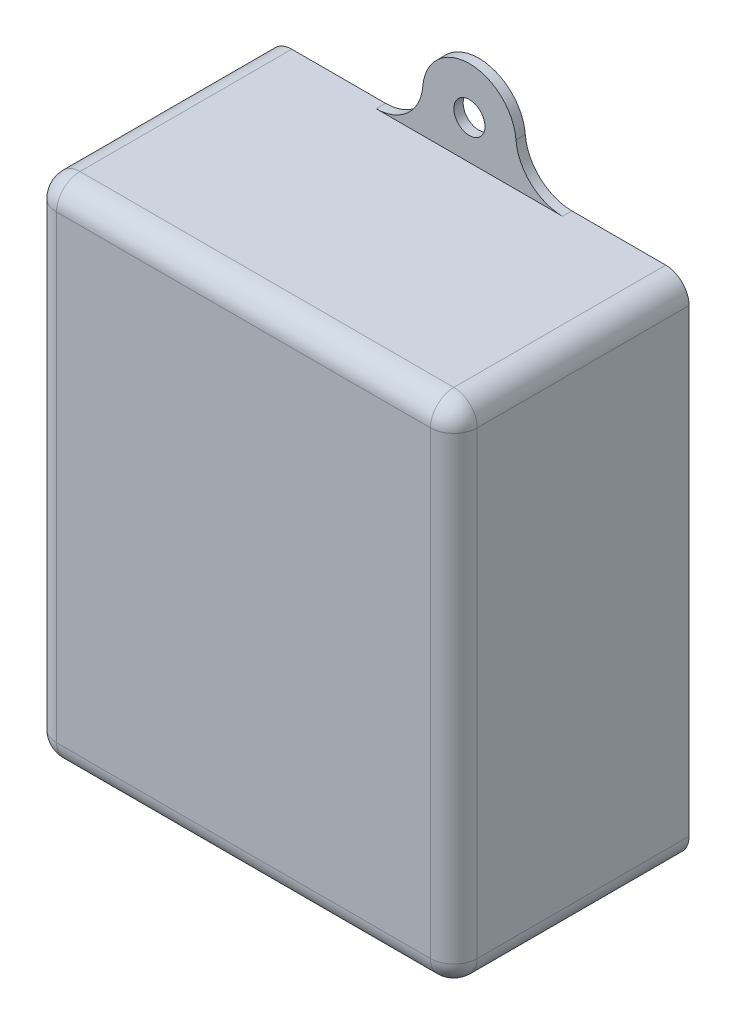
SolidWorks part; units mm, degrees
ref_plane "前视基准面" through (0, 0, 0) normal (0, 0, 1) x (1, 0, 0)
ref_plane "上视基准面" through (0, 0, 0) normal (0, 1, 0) x (1, 0, 0)
ref_plane "右视基准面" through (0, 0, 0) normal (1, 0, 0) x (0, 0, -1)
sketch "草图1" plane through (0, 0, 0) normal (0, 0, 1) x (1, 0, 0)
  line L0 (-11.9583, 32.5) -> (-27, 32.5)
  line L1 (-27, 32.5) -> (-27, -32.5)
  line L3 (27, -32.5) -> (27, 32.5)
  line L4 (-62.2008, 0) -> (42.7389, 0) construction
  line L5 (0, 66.4186) -> (0, -56.2887) construction
  line L6 (11.9583, 32.5) -> (27, 32.5)
  line L7 (-11.9583, -32.5) -> (-27, -32.5)
  line L8 (11.9583, -32.5) -> (27, -32.5)
  circle A0 centre (0, 37.5) radius 2
  circle A1 centre (0, -37.5) radius 2
  arc A2 (-5.9791, 38) -> (-11.9583, 32.5) centre (-11.9583, 38.5) cw
  arc A3 (5.9791, 38) -> (11.9583, 32.5) centre (11.9583, 38.5) ccw
  arc A4 (5.9791, -38) -> (11.9583, -32.5) centre (11.9583, -38.5) cw
  arc A5 (-5.9791, -38) -> (-11.9583, -32.5) centre (-11.9583, -38.5) ccw
  arc A6 (5.9791, 38) -> (-5.9791, 38) centre (0, 37.5) ccw
  arc A7 (5.9791, -38) -> (-5.9791, -38) centre (0, -37.5) cw
  dimension "D3" = 4
  dimension "D4" = 6
  dimension "D6" = 75
  dimension "D2" = 6
  dimension "D1" = 54
  dimension "D5" = 65
extrude "拉伸1" add sketch "草图1" along normal blind 1.2
sketch "草图5" plane through (0, 0, 1.2) normal (0, 0, 1) x (1, 0, 0)
  line L1 (-27, 32.5) -> (27, 32.5)
  line L2 (-27, 32.5) -> (-27, -32.5)
  line L3 (-27, -32.5) -> (27, -32.5)
  line L4 (27, 32.5) -> (27, -32.5)
extrude "拉伸2" add sketch "草图5" along normal blind 29
fillet "圆角1" radius 3 8 edges at (0, 32.5, 30.2) (27, 0, 30.2) (0, -32.5, 30.2) (-27, 0, 30.2) (-27, 32.5, 15.1) (-27, -32.5, 15.1) (27, -32.5, 15.1) (27, 32.5, 15.1)
